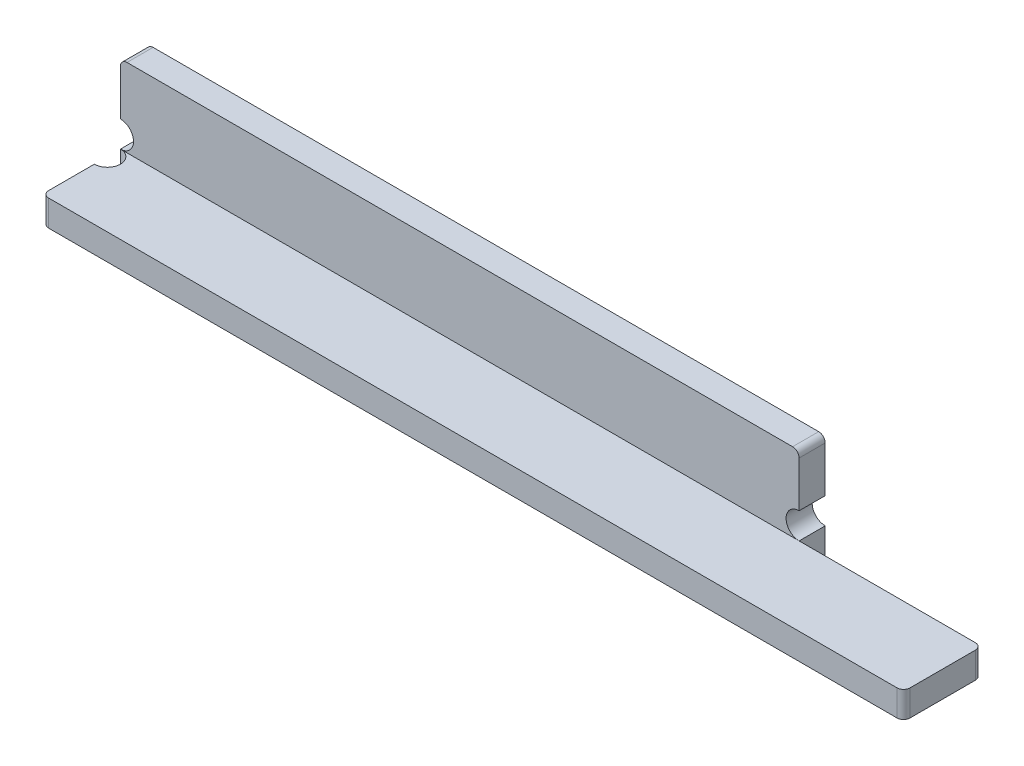
SolidWorks part; units mm, degrees
material "PET"
ref_plane "Front Plane" through (0, 0, 0) normal (0, 0, 1) x (1, 0, 0)
ref_plane "Top Plane" through (0, 0, 0) normal (0, 1, 0) x (1, 0, 0)
ref_plane "Right Plane" through (0, 0, 0) normal (1, 0, 0) x (0, 0, -1)
sketch "Sketch1" plane through (0, 0, 0) normal (0, 1, 0) x (1, 0, 0)
  line L0 (0, 0) -> (0, 17.5)
  line L1 (0, 17.5) -> (85, 17.5)
  line L2 (85, 17.5) -> (85, 2.5)
  line L3 (85, 2.5) -> (130, 2.5)
  line L4 (130, 2.5) -> (130, -2.5)
  line L5 (130, -2.5) -> (165, -2.5)
  line L6 (165, -2.5) -> (165, -17.5)
  line L7 (165, -17.5) -> (0, -17.5)
  line L8 (0, -17.5) -> (0, 0)
  dimension "D1" = 5
  dimension "D2" = 15
  dimension "D3" = 165
  dimension "D4" = 130
  dimension "D5" = 85
extrude "base" add sketch "Sketch1" along normal blind 5
sketch "Sketch2" plane through (0, 5, 0) normal (0, 1, 0) x (1, 0, 0)
  line L0 (0, 17.5) -> (0, -17.5) construction
  line L1 (130, 2.5) -> (0, 2.5)
  line L2 (130, 2.5) -> (130, -2.5)
  line L3 (130, -2.5) -> (0, -2.5)
  line L4 (0, 2.5) -> (0, -2.5)
  line L5 (165, -2.5) -> (130, -2.5) construction
extrude "middle_extrusion" add sketch "Sketch2" along normal blind 15
sketch "Sketch3" plane through (0, 5, 0) normal (0, 1, 0) x (1, 0, 0)
  line L0 (0, -2.5) -> (0, -17.5) construction
  line L1 (0, -7.5) -> (0, -2.5)
  line L2 (0, 2.5) -> (0, 7.5)
  line L3 (0, 17.5) -> (0, 2.5) construction
  line L4 (85, 2.5) -> (85, 7.5)
  line L5 (85, 2.5) -> (85, 17.5) construction
  arc A0 (0, -2.5) -> (0, -7.5) centre (0, -5) cw
  arc A1 (0, 2.5) -> (0, 7.5) centre (0, 5) ccw
  arc A2 (85, 2.5) -> (85, 7.5) centre (85, 5) cw
  point P3 (0, -5)
  dimension "D1" = 5
extrude "fancy_cutout" cut sketch "Sketch3" against normal through all
sketch "Sketch4" plane through (0, 0, 2.5) normal (0, 0, 1) x (1, 0, 0)
  line L0 (0, 5) -> (0, 10)
  line L1 (0, 20) -> (0, 5) construction
  line L2 (130, 5) -> (130, 10)
  line L3 (130, 20) -> (130, 5) construction
  arc A0 (0, 10) -> (0, 5) centre (0, 7.5) cw
  arc A1 (130, 10) -> (130, 5) centre (130, 7.5) ccw
  point P12 (0, 7.5)
  dimension "D1" = 5
extrude "fancy_cutout_middle" cut sketch "Sketch4" against normal through all
fillet "overall_fillets" radius 1.25 7 edges at (0, 2.5, -17.5) (85, 2.5, -17.5) (165, 2.5, 2.5) (165, 2.5, 17.5) (0, 2.5, 17.5) (130, 20, 0) (0, 20, 0)
